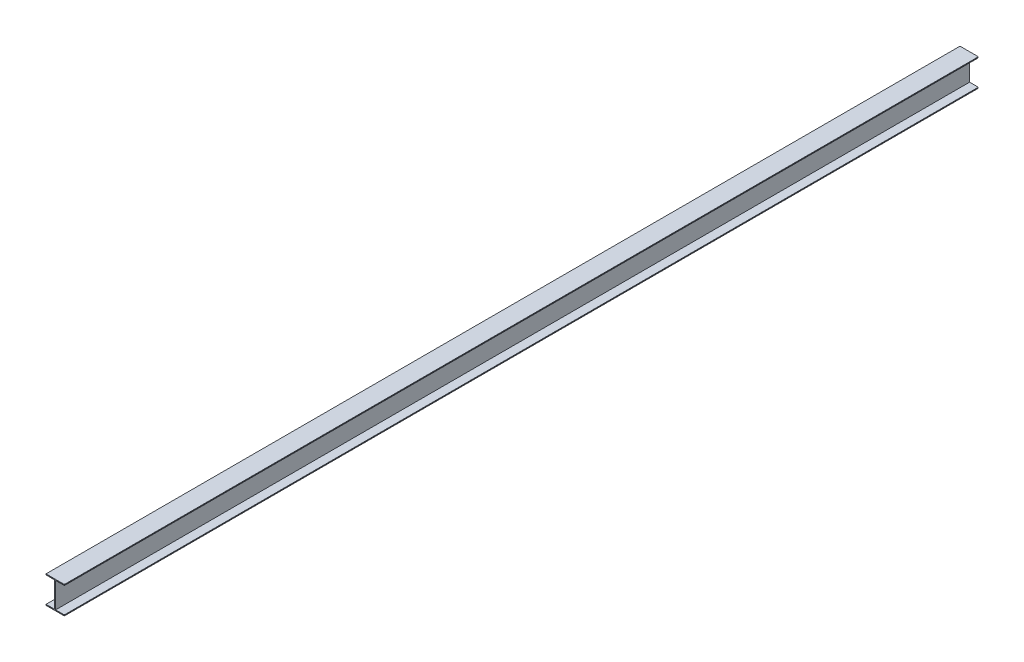
SolidWorks part; units mm, degrees
material "ASTM A992 Steel"
ref_plane "Front" through (0, 0, 0) normal (0, 0, 1) x (1, 0, 0)
ref_plane "Top" through (0, 0, 0) normal (0, 1, 0) x (1, 0, 0)
ref_plane "Right" through (0, 0, 0) normal (1, 0, 0) x (0, 0, -1)
sketch "Sketch1" plane through (0, 0, 0) normal (0, 0, 1) x (1, 0, 0)
  line L0 (0, -0.0002) -> (101.6, -0.0002)
  line L1 (101.6, -0.0002) -> (101.6, -7.1122)
  line L2 (101.6, -7.1122) -> (53.408, -7.1122)
  line L3 (53.408, -7.1122) -> (53.408, -146.0502)
  line L4 (53.408, -146.0502) -> (101.6, -146.0502)
  line L5 (101.6, -146.0502) -> (101.6, -153.1622)
  line L6 (101.6, -153.1622) -> (0, -153.1622)
  line L7 (0, -153.1622) -> (0, -146.0502)
  line L8 (0, -146.0502) -> (47.566, -146.0502)
  line L9 (47.566, -146.0502) -> (47.566, -7.1122)
  line L10 (47.566, -7.1122) -> (0, -7.1122)
  line L11 (0, -7.1122) -> (0, -0.0002)
  line L12 (50.8, -0.0002) -> (50.8, -153.1622) construction
  dimension "D1" = 5.842
  dimension "D2" = 7.112
  dimension "D3" = 7.112
  dimension "D4" = 7.112
  dimension "D5" = 153.162
  dimension "D6" = 50.8
  dimension "D7" = 50.8
  dimension "D8" = 47.566
extrude "Boss-Extrude1" add sketch "Sketch1" along normal blind 5062
sketch "Sketch2" plane through (0, -153.1622, 0) normal (0, -1, 0) x (1, 0, 0)
  line L0 (0, 5062) -> (0, 0) construction
  line L1 (101.6, 5062) -> (101.6, 0) construction
  line L3 (101.6, 2531) -> (101.6, 2683.4)
  line L4 (101.6, 2683.4) -> (-279.5172, 2683.4)
  line L5 (-279.5172, 2607.2) -> (-279.5172, 2683.4)
  line L8 (101.6, 2531) -> (101.6, 2378.6)
  line L9 (101.6, 2378.6) -> (-279.5172, 2378.6)
  line L10 (-279.5172, 2607.2) -> (-279.5172, 2378.6)
  point P0 (0, 2531)
  dimension "D1" = 152.4
  dimension "D2" = 152.4
split line "Split Line1"
fillet "Fillet1" radius 3.175 4 edges at (101.6, -3.5562, 5062) (101.6, -149.6062, 5062) (101.6, -149.6062, 0) (101.6, -3.5562, 0)
fillet "Fillet2" radius 3.175 11 edges at (0, -153.1622, 1189.3) (0, -153.1622, 2531) (0, -153.1622, 3872.7) (49.2125, -153.1622, 0) (100.6701, -153.1622, 0.9299) (101.6, -153.1622, 1190.8875) (101.6, -153.1622, 3871.1125) (101.6, -153.1622, 2607.2) (101.6, -153.1622, 2454.8) (100.6701, -153.1622, 5061.0701) (49.2125, -153.1622, 5062)
fillet "Fillet3" radius 3.175 8 edges at (75.9165, -7.1122, 0) (100.6701, -7.1122, 0.9299) (101.6, -7.1122, 2531) (100.6701, -7.1122, 5061.0701) (23.783, -7.1122, 0) (0, -7.1122, 2531) (75.9165, -7.1122, 5062) (23.783, -7.1122, 5062)
